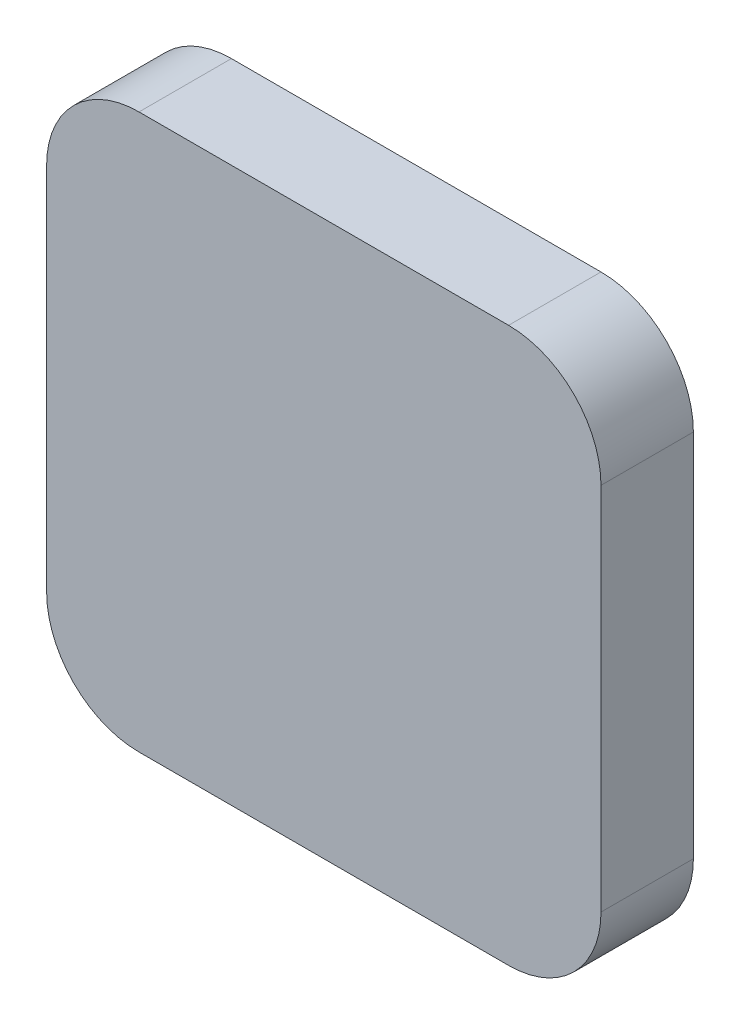
SolidWorks part; units mm, degrees
ref_plane "Plano frontal" through (0, 0, 0) normal (0, 0, 1) x (1, 0, 0)
ref_plane "Plano superior" through (0, 0, 0) normal (0, 1, 0) x (1, 0, 0)
ref_plane "Plano direito" through (0, 0, 0) normal (1, 0, 0) x (0, 0, -1)
sketch "Esboço1" plane through (0, 0, 0) normal (0, 0, 1) x (1, 0, 0)
  line L1 (6, -6) -> (-6, -6)
  line L2 (6, -6) -> (6, 6)
  line L3 (6, 6) -> (-6, 6)
  line L4 (-6, -6) -> (-6, 6)
  line L5 (6, -6) -> (-6, 6) construction
  line L6 (6, 6) -> (-6, -6) construction
  point P0 (0, 0)
  dimension "D1" = 12
  dimension "D2" = 12
extrude "Ressalto-extrusão1" add sketch "Esboço1" along normal blind 2
fillet "Filete1" radius 2 4 edges at (-6, 6, 1) (-6, -6, 1) (6, -6, 1) (6, 6, 1)
